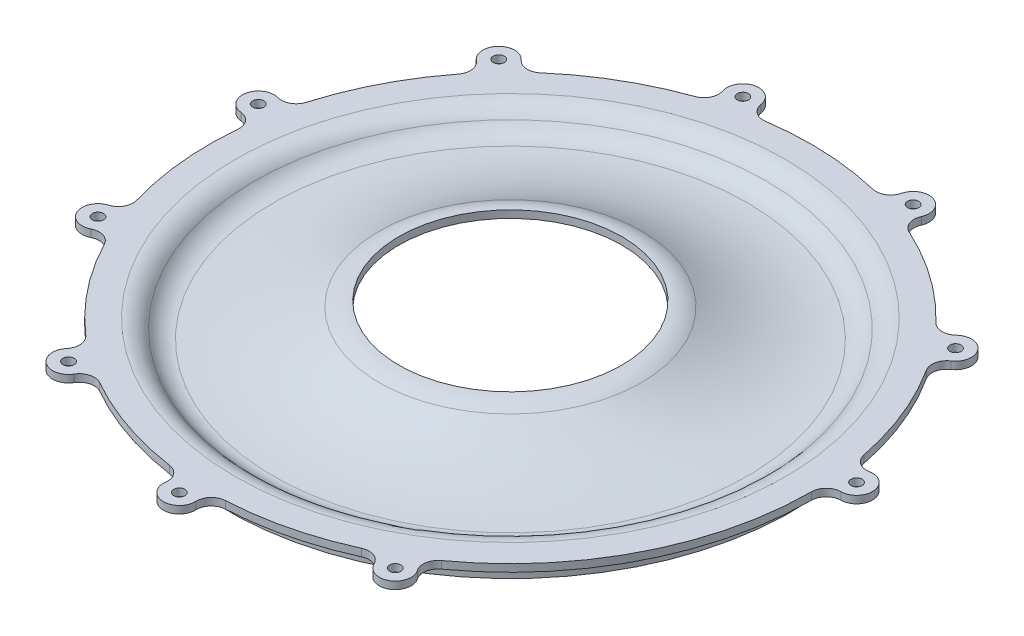
SolidWorks part; units mm, degrees
ref_plane "Front Plane" through (0, 0, 0) normal (0, 0, 1) x (1, 0, 0)
ref_plane "Top Plane" through (0, 0, 0) normal (0, 1, 0) x (1, 0, 0)
ref_plane "Right Plane" through (0, 0, 0) normal (1, 0, 0) x (0, 0, -1)
sketch "Sketch1" plane through (0, 0, 0) normal (0, 0, 1) x (1, 0, 0)
  line L0 (0, -11) -> (0, 21.479) construction
  line L1 (-75, 8) -> (-63.75, 8)
  line L2 (63.75, 8) -> (75, 8)
  line L4 (-75, 8) -> (-63.75, 8)
  line L12 (75, 8) -> (63.75, 8)
  line L15 (63.75, 9) -> (75, 9)
  line L17 (30, 16) -> (30, 18) construction
  line L19 (33.8293, 16) -> (34.3283, 16.8666) construction
  line L20 (30, 18) -> (30, 20)
  line L24 (30, 18) -> (30, 17)
  line L28 (74, 16) -> (76, 14) construction
  line L29 (63.75, 9) -> (63.75, 10.9999) construction
  line L30 (35.3264, 18.5996) -> (34.3283, 16.8666) construction
  line L32 (75, 9) -> (76, 9)
  line L33 (76, 9) -> (76, 14)
  line L34 (76, 14) -> (81, 14)
  line L35 (81, 14) -> (81, 16)
  line L36 (81, 16) -> (74, 16)
  line L37 (76, -1) -> (76, 9) construction
  arc A0 (-63.75, 8) -> (-33.8293, 16) centre (-63.75, 67.9531) ccw
  arc A1 (33.8293, 16) -> (63.75, 8) centre (63.75, 67.9531) ccw
  arc A3 (-63.75, 8) -> (-33.8293, 16) centre (-63.75, 67.9531) ccw
  arc A9 (63.75, 8) -> (33.8293, 16) centre (63.75, 67.9531) cw
  arc A10 (63.75, 10.9999) -> (35.3264, 18.5996) centre (63.75, 67.9531) cw
  arc A11 (34.3283, 16.8666) -> (63.75, 9) centre (63.75, 67.9531) ccw
  arc A12 (30, 18) -> (34.3283, 16.8666) centre (30.0875, 9.5029) cw
  arc A13 (30, 20) -> (35.3264, 18.5996) centre (30.0875, 9.5029) cw
  arc A15 (68.875, 13.5) -> (74, 16) centre (74, 9.4969) cw
  arc A16 (63.75, 10.9999) -> (68.875, 13.5) centre (63.75, 17.503) ccw
  spline S0 degree 3 poles (2670.9881, 1313.3785) (-225.1109, -94.4912) (-31.1852, 22.9606) (-28.9065, 13.0977) (-71.8006, -27.2431) (-1341.1358, 2713.6505) knots -5.426091 -5.426091 -5.426091 -5.426091 0.770699 0.870699 4.381945 4.381945 4.381945 4.381945 only from (-33.8293, 16) to (-30, 16)
  spline S1 degree 3 poles (2590.216, 5441.0193) (96.0924, -49.8104) (28.6959, 12.1861) (31.5341, 24.4706) (328.551, -157.5506) (-5366.7973, 2628.6418) knots -4.288492 -4.288492 -4.288492 -4.288492 0.129301 0.229301 7.927742 7.927742 7.927742 7.927742 only from (30, 16) to (33.8293, 16)
  spline S2 degree 3 poles (33.8293, 16) (33.8068, 16.0129) (29.9246, 17.5042) (29.6923, 16.4986) (29.8153, 16.12) (30, 16) knots 0 0 0 0 0.770699 0.870699 1 1 1 1
  spline S3 degree 3 poles (-33.8293, 16) (-33.8068, 16.0129) (-29.9246, 17.5042) (-29.6923, 16.4986) (-29.8153, 16.12) (-30, 16) knots 0 0 0 0 0.770699 0.870699 1 1 1 1
  point P26 (68.6182, 13.5)
  point P32 (0, 0)
  point P37 (71.0204, 14)
  dimension "D2" = 2
  dimension "D1" = 1
  dimension "D5" = 1
  dimension "D3" = 45
  dimension "D4" = 2
revolve "Revolve2" add sketch "Sketch1" angle 360 about L0
sketch "Sketch2" plane through (0, 16, 0) normal (0, 1, 0) x (1, 0, 0)
  arc A1 (69.2965, 49.2885) -> (68.1415, 43.7919) centre (71.5066, 45.9545) ccw construction
  arc A13 (69.2965, 49.2885) -> (64.0019, 55.9922) centre (66.9285, 52.8609) ccw construction
  arc A14 (58.3872, 56.142) -> (64.0019, 55.9922) centre (61.2706, 58.9145) ccw construction
  arc A15 (69.2965, 49.2885) -> (68.1415, 43.7919) centre (71.5066, 45.9545) ccw
  arc A16 (69.2965, 49.2885) -> (64.0019, 55.9922) centre (66.9285, 52.8609) ccw
  arc A17 (58.3872, 56.142) -> (64.0019, 55.9922) centre (61.2706, 58.9145) ccw
  arc A18 (58.3872, 56.142) -> (68.1415, 43.7919) centre (0, 0) cw
  circle A19 centre (66.9285, 52.8609) radius 1.5
  dimension "D2" = 3
extrude "Boss-Extrude1" add sketch "Sketch2" against normal up to surface (2 mm away)
pattern_circular "CirPattern1" count 11 over 360 about axis through (0, 0, 0) along (0, 1, 0) skipping 2 of "Boss-Extrude1"
equation "\"Clearance\"= 1mm"
equation "\"D1@Sketch1\"= \"Clearance\""
equation "\"Wall Thickness\"= 5mm"
equation "\"Bolt Diameter\"= 3mm"
equation "\"D5@Sketch1\"=\"Clearance\""
equation "\"D2@Sketch2\"=\"Bolt Diameter\""
